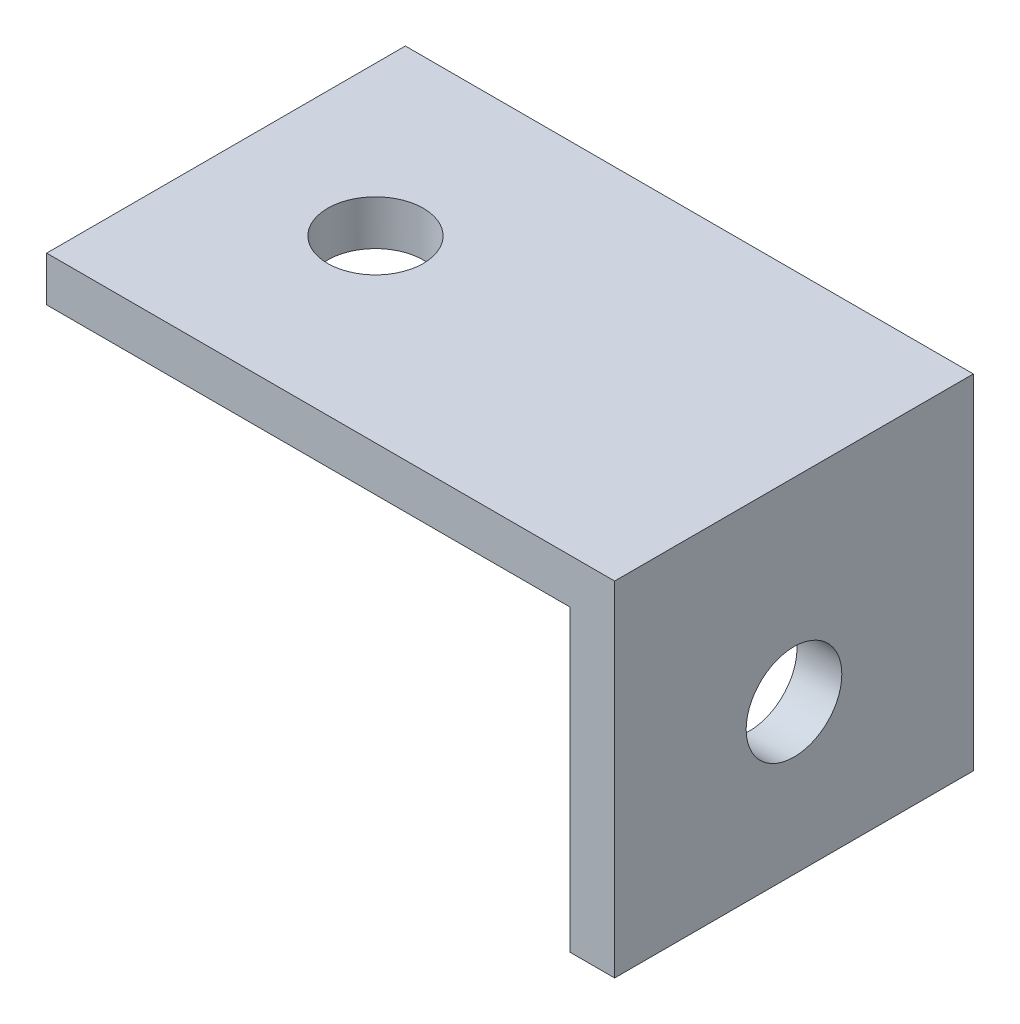
SolidWorks part; units mm, degrees
material "碳纤维板_1600kg_m3"
ref_plane "前视基准面" through (0, 0, 0) normal (0, 0, 1) x (1, 0, 0)
ref_plane "上视基准面" through (0, 0, 0) normal (0, 1, 0) x (1, 0, 0)
ref_plane "右视基准面" through (0, 0, 0) normal (1, 0, 0) x (0, 0, -1)
other "Configuration Table"
sketch "草图1" plane through (0, 0, 0) normal (0, 0, 1) x (1, 0, 0)
  line L0 (-5, 0) -> (12.5, 0)
  line L1 (12.5, 0) -> (12.5, -10)
  line L2 (12.5, -10) -> (14, -10)
  line L3 (14, -10) -> (14, 1.5)
  line L4 (14, 1.5) -> (-5, 1.5)
  line L5 (-5, 1.5) -> (-5, 0)
extrude "1p5mm直角固定座_宽12" add sketch "草图1" along normal blind 12
sketch "草图2" plane through (0, 0, 0) normal (0, 1, 0) x (1, 0, 0)
  circle A0 centre (0, -6) radius 1.6
extrude "水平脚面M3孔" cut sketch "草图2" along normal blind 100 and the other way blind 100
sketch "草图3" plane through (0, 0, 0) normal (1, 0, 0) x (0, 0, -1)
  circle A0 centre (-6, -5) radius 1.6
extrude "竖向法兰M3孔" cut sketch "草图3" along normal blind 100 and the other way blind 100
